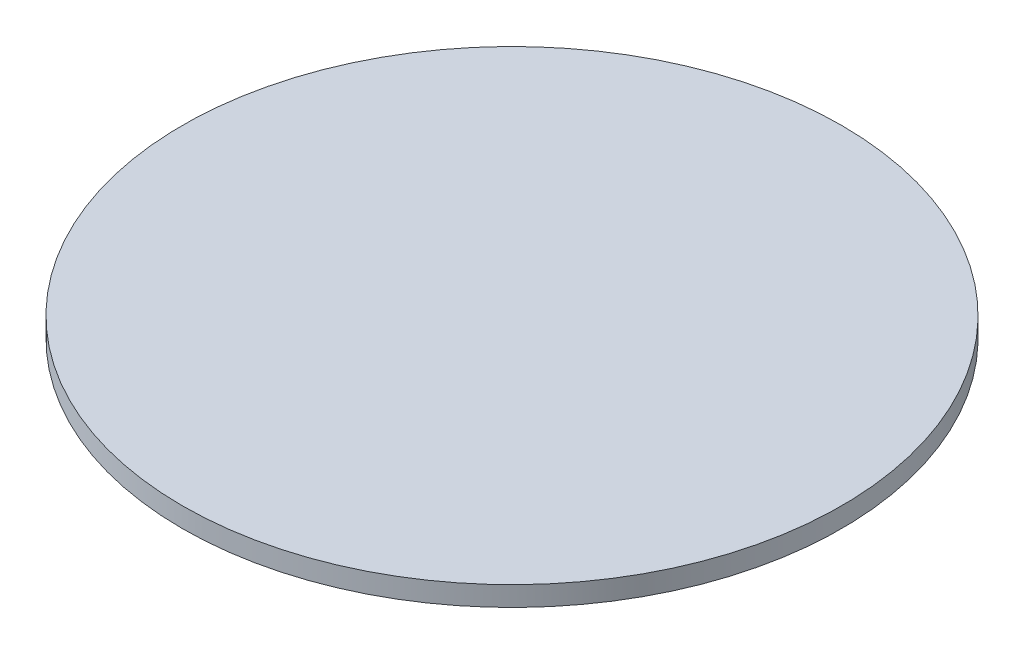
SolidWorks part; units mm, degrees
ref_plane "Front Plane" through (0, 0, 0) normal (0, 0, 1) x (1, 0, 0)
ref_plane "Top Plane" through (0, 0, 0) normal (0, 1, 0) x (1, 0, 0)
ref_plane "Right Plane" through (0, 0, 0) normal (1, 0, 0) x (0, 0, -1)
sketch "Sketch1" plane through (0, 0, 0) normal (0, 1, 0) x (1, 0, 0)
  circle A0 centre (0, 0) radius 50
  dimension "D1" = 100
extrude "Boss-Extrude1" add sketch "Sketch1" along normal blind 3
sketch "Sketch2" plane through (0, 0, 0) normal (0, -1, 0) x (1, 0, 0)
  circle A0 centre (0, 0) radius 4
  circle A1 centre (0, 0) radius 2.5
  dimension "D1" = 5
  dimension "D2" = 8
extrude "Boss-Extrude2" add sketch "Sketch2" along normal blind 6
